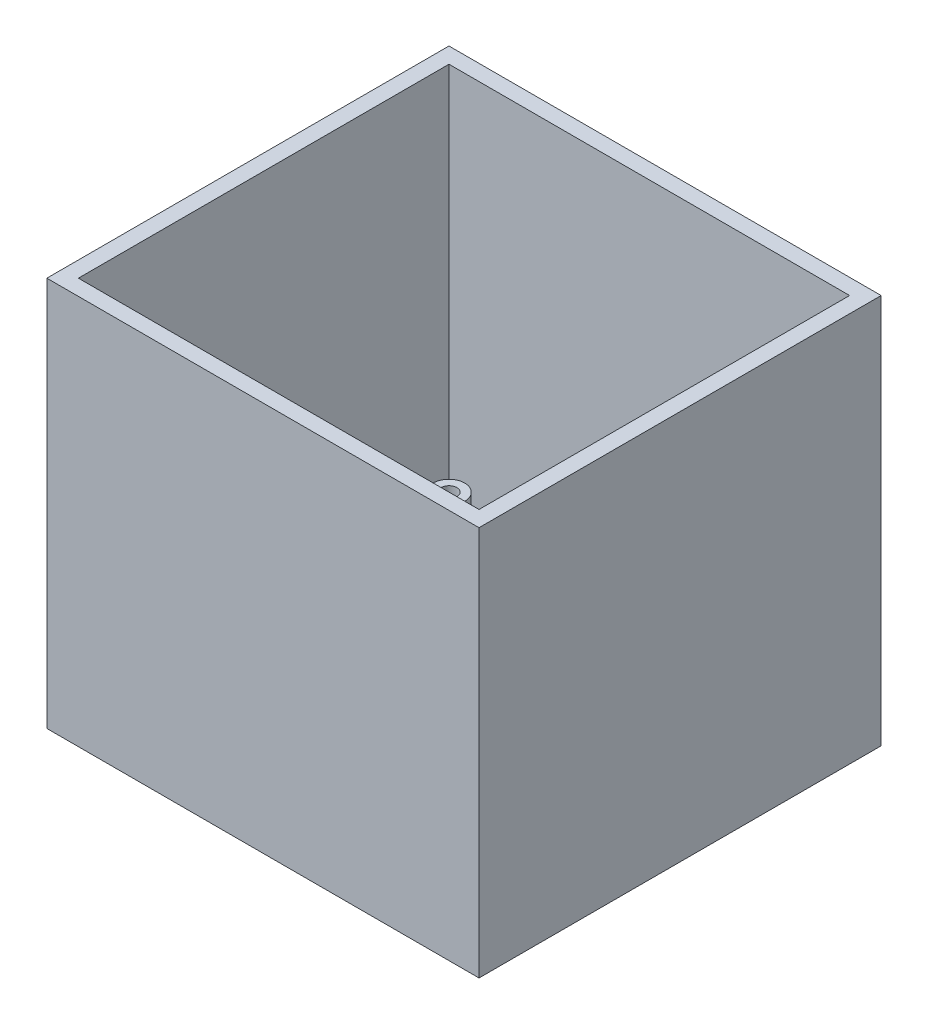
SolidWorks part; units mm, degrees
ref_plane "Front Plane" through (0, 0, 0) normal (0, 0, 1) x (1, 0, 0)
ref_plane "Top Plane" through (0, 0, 0) normal (0, 1, 0) x (1, 0, 0)
ref_plane "Right Plane" through (0, 0, 0) normal (1, 0, 0) x (0, 0, -1)
sketch "Sketch1" plane through (0, 0, 0) normal (0, 1, 0) x (1, 0, 0)
  line L1 (-27.4, -25.495) -> (27.4, -25.495)
  line L2 (-27.4, -25.495) -> (-27.4, 25.495)
  line L3 (-27.4, 25.495) -> (27.4, 25.495)
  line L4 (27.4, -25.495) -> (27.4, 25.495)
  line L5 (-27.4, -25.495) -> (27.4, 25.495) construction
  line L6 (-27.4, 25.495) -> (27.4, -25.495) construction
  point P0 (0, 0)
  dimension "D1" = 50.99
  dimension "D2" = 54.8
extrude "Boss-Extrude2" add sketch "Sketch1" along normal blind 2
sketch "Sketch2" plane through (0, 2, 0) normal (0, 1, 0) x (1, 0, 0)
  line L0 (-22.86, 20.955) -> (22.86, 20.955) construction
  line L1 (-22.86, -20.955) -> (22.86, -20.955) construction
  line L2 (-22.86, -20.955) -> (-22.86, 20.955) construction
  line L3 (-22.86, 20.955) -> (22.86, 20.955) construction
  line L4 (22.86, -20.955) -> (22.86, 20.955) construction
  line L5 (-22.86, -20.955) -> (22.86, 20.955) construction
  line L6 (-22.86, 20.955) -> (22.86, -20.955) construction
  circle A0 centre (-22.86, 20.955) radius 2
  circle A1 centre (-22.86, 20.955) radius 1
  circle A2 centre (22.86, 20.955) radius 1
  circle A3 centre (22.86, 20.955) radius 2
  circle A4 centre (22.86, -20.955) radius 1
  circle A5 centre (22.86, -20.955) radius 2
  circle A6 centre (-22.86, -20.955) radius 1
  circle A7 centre (-22.86, -20.955) radius 2
  point P0 (0, 0)
  dimension "D3" = 2
  dimension "D1" = 45.72
  dimension "D2" = 41.91
  dimension "D5" = 45.72
  dimension "D4" = 2
extrude "Boss-Extrude3" add sketch "Sketch2" along normal blind 3
sketch "Sketch3" plane through (0, 2, 0) normal (0, 1, 0) x (1, 0, 0)
  line L1 (-25.4, -23.495) -> (25.4, -23.495)
  line L2 (-25.4, -23.495) -> (-25.4, 23.495)
  line L3 (-25.4, 23.495) -> (25.4, 23.495)
  line L4 (25.4, -23.495) -> (25.4, 23.495)
  line L5 (-25.4, -23.495) -> (25.4, 23.495) construction
  line L6 (-25.4, 23.495) -> (25.4, -23.495) construction
  line L7 (-27.4, 25.495) -> (-27.4, -25.495) construction
  line L8 (27.4, 25.495) -> (-27.4, 25.495) construction
  line L10 (-27.4, -25.495) -> (27.4, -25.495)
  line L11 (-27.4, -25.495) -> (-27.4, 25.495)
  line L12 (-27.4, 25.495) -> (27.4, 25.495)
  line L13 (27.4, -25.495) -> (27.4, 25.495)
  line L14 (-27.4, -25.495) -> (27.4, 25.495) construction
  line L15 (-27.4, 25.495) -> (27.4, -25.495) construction
  point P0 (0, 0)
  point P10 (0, 0)
  dimension "D1" = 2
  dimension "D2" = 2
extrude "Boss-Extrude5" add sketch "Sketch3" along normal blind 47.45
